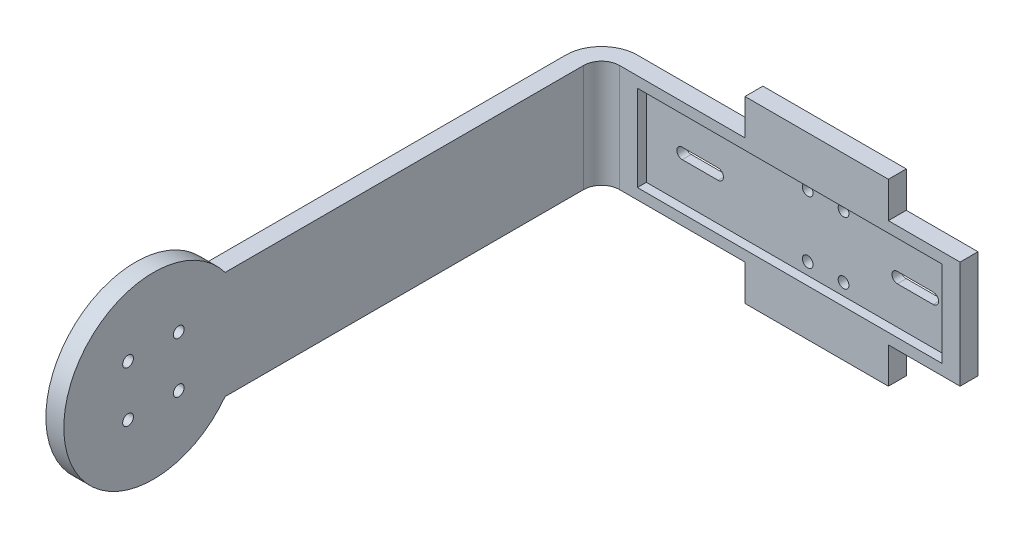
SolidWorks part; units mm, degrees
material "Titanium Ti-8Mn, Annealed"
ref_plane "Front Plane" through (0, 0, 0) normal (0, 0, 1) x (1, 0, 0)
ref_plane "Top Plane" through (0, 0, 0) normal (0, 1, 0) x (1, 0, 0)
ref_plane "Right Plane" through (0, 0, 0) normal (1, 0, 0) x (0, 0, -1)
sketch "Sketch1" plane through (0, 0, 0) normal (0, 1, 0) x (1, 0, 0)
  line L6 (0, -5) -> (0, -125)
  line L7 (5, 0) -> (100, 0)
  line L8 (5, 5) -> (100, 5)
  line L9 (-5, -5) -> (-5, -125)
  line L10 (100, 0) -> (100, 5)
  line L11 (0, -125) -> (-5, -125)
  arc A2 (5, 0) -> (0, -5) centre (5, -5) ccw
  arc A3 (5, 5) -> (-5, -5) centre (5, -5) ccw
  point P6 (0, 0)
  dimension "D3" = 5
  dimension "D1" = 100
  dimension "D2" = 125
  dimension "D4" = 5
extrude "Boss-Extrude1" add sketch "Sketch1" against normal blind 30
sketch "Sketch4" plane through (0, 0, 0) normal (1, 0, 0) x (0, 0, -1)
  line L1 (-125, 0) -> (-5, 0) construction
  line L3 (-125, -30) -> (-125, 0) construction
  circle A0 centre (-125, -15) radius 25
  dimension "D1" = 50
  dimension "D2" = 0
  dimension "D3" = 15
extrude "Boss-Extrude3" add sketch "Sketch4" against normal blind 5
sketch "Sketch8" plane through (0, 0, 0) normal (0, 0, 1) x (1, 0, 0)
  line L1 (-5, -30) -> (-5, 0) construction
  line L5 (5, 0) -> (100, 0) construction
  line L6 (5, -30) -> (100, -30) construction
  line L9 (100, -30) -> (100, 0) construction
  line L10 (95, -3) -> (10, -3)
  line L11 (95, -3) -> (95, -27)
  line L12 (95, -27) -> (10, -27)
  line L13 (10, -3) -> (10, -27)
  dimension "D1" = 5
  dimension "D2" = 15
  dimension "D3" = 3
  dimension "D4" = 3
extrude "Cut-Extrude2" cut sketch "Sketch8" against normal blind 2.5
sketch "Sketch11" plane through (-5, 0, 0) normal (-1, 0, 0) x (0, 0, 1)
  line L1 (125, 10) -> (125, -40) construction
  line L2 (125, -15) -> (150, -15) construction
  line L3 (125, -15) -> (132.0711, -7.9289) construction
  arc A7 (105, -30) -> (105, 0) centre (125, -15) ccw construction
  circle A8 centre (125, -15) radius 10 construction
  circle A10 centre (132.0711, -7.9289) radius 1.5
  circle A11 centre (132.0711, -22.0711) radius 1.5
  circle A12 centre (117.9289, -22.0711) radius 1.5
  circle A13 centre (117.9289, -7.9289) radius 1.5
  point P20 (125, -15)
  dimension "D1" = 20
  dimension "D3" = 3
  dimension "D2" = 45
  dimension "D4" = 4
extrude "Cut-Extrude4" cut sketch "Sketch11" against normal up to surface (5 mm away) up to face at (0, -15, 66.25)
sketch "Sketch12" plane through (0, 0, -5) normal (0, 0, -1) x (-1, 0, 0)
  line L0 (-100, 0) -> (-5, 0) construction
  line L1 (-80, 0) -> (-40, 0)
  line L2 (-80, 0) -> (-80, 10)
  line L3 (-80, 10) -> (-40, 10)
  line L4 (-40, 0) -> (-40, 10)
  line L5 (-100, -30) -> (-100, 0) construction
  line L6 (-100, -15) -> (18.2822, -15) construction
  line L7 (-40, -30) -> (-40, -40)
  line L8 (-80, -40) -> (-40, -40)
  line L9 (-80, -30) -> (-80, -40)
  line L10 (-80, -30) -> (-40, -30)
  point P8 (-60, 10)
  dimension "D1" = 40
  dimension "D2" = 20
  dimension "D3" = 10
extrude "Boss-Extrude5" add sketch "Sketch12" against normal blind 5
sketch "Sketch13" plane through (0, 0, -2.5) normal (0, 0, 1) x (1, 0, 0)
  line L0 (90, -15) -> (80, -15) construction
  line L1 (90, -16.5) -> (80, -16.5)
  line L2 (90, -13.5) -> (80, -13.5)
  line L3 (100, -30) -> (100, 0) construction
  line L4 (100, -15) -> (10, -15) construction
  line L5 (10, -3) -> (10, -27) construction
  line L6 (55, -15) -> (55, 16.2228) construction
  line L7 (20, -15) -> (30, -15) construction
  line L8 (20, -16.5) -> (30, -16.5)
  line L9 (20, -13.5) -> (30, -13.5)
  arc A0 (90, -16.5) -> (90, -13.5) centre (90, -15) ccw
  arc A1 (80, -13.5) -> (80, -16.5) centre (80, -15) ccw
  arc A2 (20, -16.5) -> (20, -13.5) centre (20, -15) cw
  arc A3 (30, -13.5) -> (30, -16.5) centre (30, -15) cw
  point P2 (85, -15)
  point P10 (100, -15)
  point P18 (25, -15)
  dimension "D1" = 10
  dimension "D2" = 3
  dimension "D3" = 10
extrude "Cut-Extrude5" cut sketch "Sketch13" against normal up to surface (2.5 mm away) up to face at (57.5, -15, -5)
sketch "Sketch14" plane through (0, 0, -5) normal (0, 0, -1) x (-1, 0, 0)
  line L0 (-60, 10) -> (-60, -40) construction
  line L1 (-40, 10) -> (-80, 10) construction
  line L2 (-80, -40) -> (-40, -40) construction
  line L3 (-60, -15) -> (-70, -15) construction
  line L4 (-60, -15) -> (-55, -23.6603) construction
  line L5 (-60, -15) -> (-55, -6.3397) construction
  line L6 (-60, -15) -> (-65, -23.6603) construction
  line L7 (-60, -15) -> (-65, -6.3397) construction
  circle A0 centre (-60, -15) radius 10 construction
  circle A2 centre (-65, -6.3397) radius 1.5
  circle A3 centre (-55, -6.3397) radius 1.5
  circle A5 centre (-55, -23.6603) radius 1.5
  circle A6 centre (-65, -23.6603) radius 1.5
  point P19 (-60, -15)
  point P23 (-60, -15)
  dimension "D1" = 20
  dimension "D2" = 30
  dimension "D6" = 3
  dimension "D3" = 30
  dimension "D4" = 30
  dimension "D5" = 30
extrude "Cut-Extrude6" cut sketch "Sketch14" against normal through all
